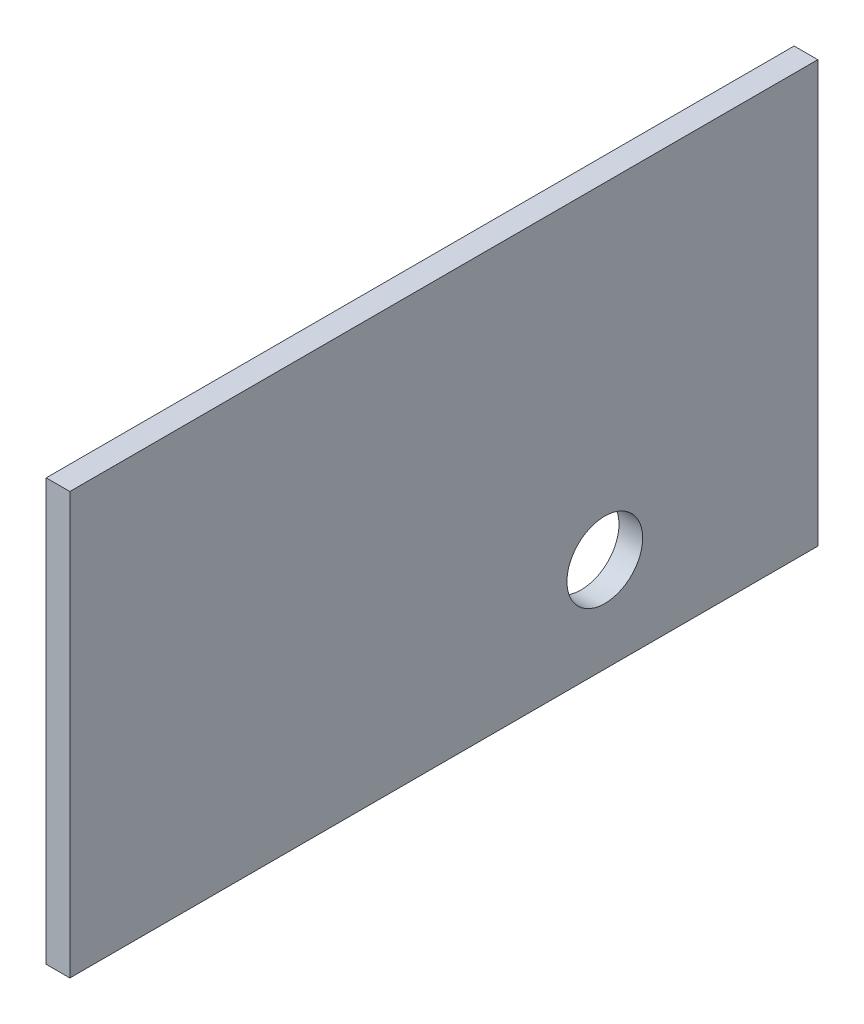
SolidWorks part; units mm, degrees
ref_plane "Front Plane" through (0, 0, 0) normal (0, 0, 1) x (1, 0, 0)
ref_plane "Top Plane" through (0, 0, 0) normal (0, 1, 0) x (1, 0, 0)
ref_plane "Right Plane" through (0, 0, 0) normal (1, 0, 0) x (0, 0, -1)
sketch "Sketch1" plane through (0, 0, 0) normal (1, 0, 0) x (0, 0, -1)
  line L1 (0, 0) -> (158, 0)
  line L2 (0, 0) -> (0, -89)
  line L3 (0, -89) -> (158, -89)
  line L4 (158, 0) -> (158, -89)
  dimension "D1" = 158
  dimension "D2" = 89
extrude "Boss-Extrude1" add sketch "Sketch1" along normal blind 5
sketch "Sketch2" plane through (5, 0, 0) normal (1, 0, 0) x (0, 0, -1)
  line L0 (158, -89) -> (158, 0) construction
  line L1 (0, -89) -> (158, -89) construction
  circle A0 centre (113, -69) radius 8
  point P2 (0, 0)
  point P5 (0, 0)
  dimension "D1" = 16
  dimension "D2" = 45
  dimension "D3" = 20
extrude "Cut-Extrude1" cut sketch "Sketch2" against normal blind 5
